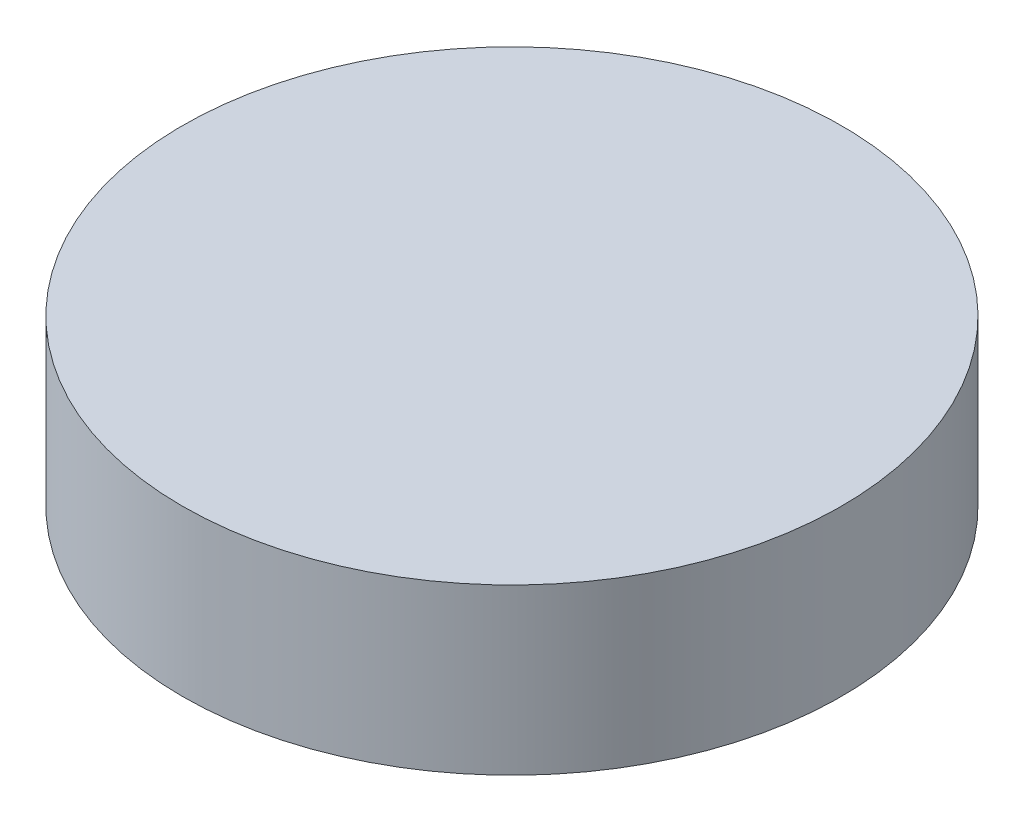
SolidWorks part; units mm, degrees
ref_plane "Front Plane" through (0, 0, 0) normal (0, 0, 1) x (1, 0, 0)
ref_plane "Top Plane" through (0, 0, 0) normal (0, 1, 0) x (1, 0, 0)
ref_plane "Right Plane" through (0, 0, 0) normal (1, 0, 0) x (0, 0, -1)
sketch "Sketch1" plane through (0, 0, 0) normal (0, 1, 0) x (1, 0, 0)
  circle A0 centre (-2.0411, 0.185) radius 2
  dimension "D1" = 4
extrude "Boss-Extrude1" add sketch "Sketch1" along normal blind 1
